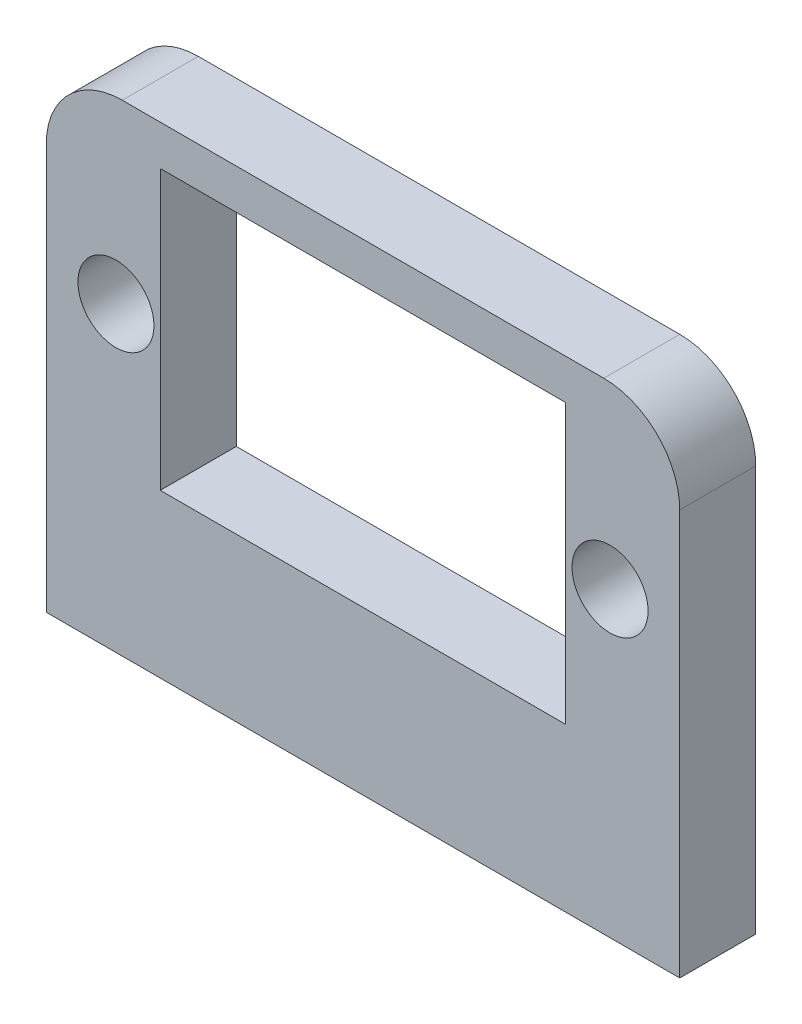
SolidWorks part; units mm, degrees
ref_plane "Front Plane" through (0, 0, 0) normal (0, 0, 1) x (1, 0, 0)
ref_plane "Top Plane" through (0, 0, 0) normal (0, 1, 0) x (1, 0, 0)
ref_plane "Right Plane" through (0, 0, 0) normal (1, 0, 0) x (0, 0, -1)
sketch "Sketch3" plane through (0, 0, 0) normal (0, 1, 0) x (1, 0, 0)
  line L0 (84.4541, 599.5572) -> (574.4541, 599.5572) construction
sketch "Sketch2" plane through (0, 0, 0) normal (0, 1, 0) x (1, 0, 0)
  line L0 (0, 0) -> (0, 57.603) construction
  line L1 (-18.1438, -7.9279) -> (18.1438, -7.9279) construction
  line L2 (-18.1438, -7.9279) -> (-18.1438, 7.9279) construction
  line L3 (-18.1438, 7.9279) -> (18.1438, 7.9279) construction
  line L4 (18.1438, -7.9279) -> (18.1438, 7.9279) construction
  line L5 (-18.1438, -7.9279) -> (18.1438, 7.9279) construction
  line L6 (-18.1438, 7.9279) -> (18.1438, -7.9279) construction
  line L7 (-21.8576, -11.143) -> (21.8576, -11.143) construction
  line L8 (-21.8576, -11.143) -> (-21.8576, 11.143) construction
  line L9 (-21.8576, 11.143) -> (21.8576, 11.143) construction
  line L10 (21.8576, -11.143) -> (21.8576, 11.143) construction
  line L11 (-21.8576, -11.143) -> (21.8576, 11.143) construction
  line L12 (-21.8576, 11.143) -> (21.8576, -11.143) construction
  line L13 (-8.5, 0) -> (8.5, 0) construction
  line L14 (0, 0) -> (0, -8.8619) construction
  line L15 (-20.6395, 7.1502) -> (-17.9674, 9.1598)
  line L16 (-4.1695, 10.4244) -> (4.1695, 10.4244)
  line L17 (-1.5343, -5.6375) -> (1.5343, -5.6375)
  line L18 (-10.0901, -10.3942) -> (-7.3916, -11.6987)
  line L19 (20.6395, 7.1502) -> (17.9674, 9.1598)
  line L20 (-2.2241, 10.4244) -> (-0.6961, 13.1148)
  line L21 (-0.6961, 13.1148) -> (0, 13.358)
  line L22 (2.2241, 10.4244) -> (0.6961, 13.1148)
  line L23 (0.6961, 13.1148) -> (0, 13.358)
  line L24 (-7.3916, -11.6987) -> (-0.7757, -11.143)
  line L25 (-0.7757, -11.143) -> (0, -10.9595)
  line L26 (0.7757, -11.143) -> (0, -10.9595)
  line L27 (7.3916, -11.6987) -> (0.7757, -11.143)
  line L28 (10.0901, -10.3942) -> (7.3916, -11.6987)
  line L29 (-16.4215, -5.191) -> (-11.7373, -9.2961)
  line L30 (16.4215, -5.191) -> (11.7373, -9.2961)
  line L31 (-7.3916, -11.6987) -> (7.3916, -11.6987)
  line L33 (-32.5, -20.0045) -> (32.5, -20.0045)
  line L34 (-32.5, -20.0045) -> (-32.5, 20.0045)
  line L35 (-32.5, 20.0045) -> (32.5, 20.0045)
  line L36 (32.5, -20.0045) -> (32.5, 20.0045)
  line L37 (-32.5, -20.0045) -> (32.5, 20.0045) construction
  line L38 (-32.5, 20.0045) -> (32.5, -20.0045) construction
  arc A0 (-4.1695, 10.4244) -> (-17.9674, 9.1598) centre (-11.9148, 19.0269) cw
  arc A1 (-20.6395, 7.1502) -> (-19.3461, 0.6629) centre (-23.2364, 3.2599) cw
  arc A2 (-19.3461, 0.6629) -> (-18.559, -3.0217) centre (-15.82, -0.5102) ccw
  arc A3 (-18.559, -3.0217) -> (-13.7831, -6.7121) centre (-9.4985, 3.7682) ccw
  arc A4 (-13.7831, -6.7121) -> (-6.6237, -7.9279) centre (-4.6259, 25.5245) ccw
  arc A5 (-1.5343, -5.6375) -> (-6.6237, -7.9279) centre (-1.5343, -12.4372) ccw
  arc A7 (13.7831, -6.7121) -> (6.6237, -7.9279) centre (4.6259, 25.5245) cw
  arc A8 (18.559, -3.0217) -> (13.7831, -6.7121) centre (9.4985, 3.7682) cw
  arc A9 (19.3461, 0.6629) -> (18.559, -3.0217) centre (15.82, -0.5102) cw
  arc A10 (20.6395, 7.1502) -> (19.3461, 0.6629) centre (23.2364, 3.2599) ccw
  arc A11 (4.1695, 10.4244) -> (17.9674, 9.1598) centre (11.9148, 19.0269) ccw
  arc A12 (1.5343, -5.6375) -> (6.6237, -7.9279) centre (1.5343, -12.4372) cw
  arc A14 (-12.2767, -7.1024) -> (-11.7373, -9.2961) centre (-8.8887, -7.4325) ccw
  arc A15 (-11.7373, -9.2961) -> (-10.0901, -10.3942) centre (-8.5052, -6.2323) ccw
  arc A16 (12.2767, -7.1024) -> (11.7373, -9.2961) centre (8.8887, -7.4325) cw
  arc A17 (11.7373, -9.2961) -> (10.0901, -10.3942) centre (8.5052, -6.2323) cw
  point P0 (0, 0)
  point P6 (0, 0)
  point P34 (0, 0)
  point P45 (0, 10.4244)
  point P54 (0, -5.6375)
  point P57 (-0.2087, -5.6375)
  point P72 (0, -11.6987)
  dimension "D2" = 65
  dimension "D1" = 17
extrude "Boss-Extrude1" add sketch "Sketch2" along normal blind 2
sketch "Sketch4" plane through (0, 0, 0) normal (0, 1, 0) x (1, 0, 0)
  line L0 (0, 0) -> (0, -15.9627) construction
  line L1 (0, 0) -> (0, 46.0631) construction
scale "Scale1" bodies to scale 101 scale about centroid uniform scaling yes scale factor 2
sketch "Sketch6" plane through (0, 3, 0) normal (0, 1, 0) x (1, 0, 0)
  line L0 (0, 0) -> (0, 27.4099) construction
  circle A0 centre (-5.8515, 16.2836) radius 1.5 construction
  circle A1 centre (-5.8515, 16.2836) radius 1.5
  circle A2 centre (4.1518, 16.2836) radius 1.5 construction
  circle A3 centre (4.1518, 16.2836) radius 1.5
extrude "Cut-Extrude2" cut sketch "Sketch6" against normal blind 3
sketch "Sketch7" plane through (0, 3, 0) normal (0, 1, 0) x (1, 0, 0)
  line L0 (0, 0) -> (0, 46.0631) construction
  line L1 (-12.5, 13.1109) -> (12.5, 13.1109)
  line L2 (-12.5, 13.1109) -> (-12.5, 10.1109)
  line L3 (-12.5, 10.1109) -> (12.5, 10.1109)
  line L4 (12.5, 13.1109) -> (12.5, 10.1109)
  line L5 (-12.5, 13.1109) -> (12.5, 10.1109) construction
  line L6 (-12.5, 10.1109) -> (12.5, 13.1109) construction
  point P0 (0, 11.6109)
  dimension "D1" = 3
  dimension "D2" = 25
extrude "Boss-Extrude2" add sketch "Sketch7" along normal blind 15
sketch "Sketch8" plane through (0, 0, -10.1109) normal (0, 0, 1) x (1, 0, 0)
  line L0 (0, 2.6097) -> (0, 7.1828) construction
  line L1 (-8, 16.4174) -> (8, 16.4174)
  line L2 (-8, 16.4174) -> (-8, 5.4174)
  line L3 (-8, 5.4174) -> (8, 5.4174)
  line L4 (8, 16.4174) -> (8, 5.4174)
  circle A0 centre (-9.75, 10.9174) radius 1.5
  circle A1 centre (9.75, 10.9174) radius 1.5
  point P4 (0, 5.4174)
  point P8 (-8, 10.9174)
  dimension "D3" = 3
  dimension "D4" = 1.75
  dimension "D1" = 16
  dimension "D2" = 11
extrude "Cut-Extrude3" cut sketch "Sketch8" against normal blind 18
fillet "Fillet3" radius 3 1 edges at (-12.5, 18, -11.6109)
fillet "Fillet4" radius 3 1 edges at (12.5, 18, -11.6109)
sketch "Sketch9" plane through (0, 3, 0) normal (0, 1, 0) x (1, 0, 0)
  line L21 (-7.6951, -21.8709) -> (-7.6951, -30.6829)
  line L22 (-7.6951, -30.6829) -> (5.9954, -30.6829)
  line L23 (5.9954, -30.6829) -> (5.9954, -21.8709)
  line L24 (5.9954, -21.8709) -> (8.9954, -21.8709)
  line L25 (8.9954, -21.8709) -> (8.9954, -30.0705)
  line L26 (8.9954, -30.0705) -> (18.6231, -24.4632)
  line L27 (18.6231, -24.4632) -> (23.9122, -21.0338)
  line L28 (25.28, -18.5167) -> (25.28, -3.348)
  line L29 (24.6327, -1.4865) -> (9.0527, 18.2043)
  line L30 (6.7, 19.3428) -> (3.3097, 19.3428)
  line L31 (3.3097, 19.3428) -> (0.5459, 24.5621)
  line L32 (0.5459, 24.5621) -> (-0.8499, 25.1844)
  line L33 (-0.8499, 25.1844) -> (-2.2456, 24.5621)
  line L34 (-2.2456, 24.5621) -> (-5.0094, 19.3428)
  line L35 (-5.0094, 19.3428) -> (-8.3997, 19.3428)
  line L36 (-10.7524, 18.2043) -> (-26.3324, -1.4865)
  line L37 (-26.9797, -3.348) -> (-26.9797, -18.5167)
  line L38 (-25.6119, -21.0338) -> (-20.3228, -24.4632)
  line L39 (-20.3228, -24.4632) -> (-10.6951, -30.0705)
  line L40 (-10.6951, -30.0705) -> (-10.6951, -21.8709)
  line L41 (-10.6951, -21.8709) -> (-7.6951, -21.8709)
  line L42 (-7.6951, -21.8709) -> (-7.6951, -30.6829)
  line L43 (-7.6951, -30.6829) -> (5.9954, -30.6829)
  line L44 (5.9954, -30.6829) -> (5.9954, -21.8709)
  line L45 (5.9954, -21.8709) -> (8.9954, -21.8709)
  line L46 (8.9954, -21.8709) -> (8.9954, -30.0705)
  line L47 (8.9954, -30.0705) -> (18.6231, -24.4632)
  line L48 (18.6231, -24.4632) -> (23.9122, -21.0338)
  line L49 (25.28, -18.5167) -> (25.28, -3.348)
  line L50 (24.6327, -1.4865) -> (9.0527, 18.2043)
  line L51 (6.7, 19.3428) -> (3.3097, 19.3428)
  line L52 (3.3097, 19.3428) -> (0.5459, 24.5621)
  line L53 (0.5459, 24.5621) -> (-0.8499, 25.1844)
  line L54 (-0.8499, 25.1844) -> (-2.2456, 24.5621)
  line L55 (-2.2456, 24.5621) -> (-5.0094, 19.3428)
  line L56 (-5.0094, 19.3428) -> (-8.3997, 19.3428)
  line L57 (-10.7524, 18.2043) -> (-26.3324, -1.4865)
  line L58 (-26.9797, -3.348) -> (-26.9797, -18.5167)
  line L59 (-25.6119, -21.0338) -> (-20.3228, -24.4632)
  line L60 (-20.3228, -24.4632) -> (-10.6951, -30.0705)
  line L61 (-10.6951, -30.0705) -> (-10.6951, -21.8709)
  line L62 (-10.6951, -21.8709) -> (-7.6951, -21.8709)
  arc A6 (23.9122, -21.0338) -> (25.28, -18.5167) centre (22.28, -18.5167) ccw
  arc A7 (25.28, -3.348) -> (24.6327, -1.4865) centre (22.28, -3.348) ccw
  arc A8 (9.0527, 18.2043) -> (6.7, 19.3428) centre (6.7, 16.3428) ccw
  arc A9 (-8.3997, 19.3428) -> (-10.7524, 18.2043) centre (-8.3997, 16.3428) ccw
  arc A10 (-26.3324, -1.4865) -> (-26.9797, -3.348) centre (-23.9797, -3.348) ccw
  arc A11 (-26.9797, -18.5167) -> (-25.6119, -21.0338) centre (-23.9797, -18.5167) ccw
  arc A12 (23.9122, -21.0338) -> (25.28, -18.5167) centre (22.28, -18.5167) ccw
  arc A13 (25.28, -3.348) -> (24.6327, -1.4865) centre (22.28, -3.348) ccw
  arc A14 (9.0527, 18.2043) -> (6.7, 19.3428) centre (6.7, 16.3428) ccw
  arc A15 (-8.3997, 19.3428) -> (-10.7524, 18.2043) centre (-8.3997, 16.3428) ccw
  arc A16 (-26.3324, -1.4865) -> (-26.9797, -3.348) centre (-23.9797, -3.348) ccw
  arc A17 (-26.9797, -18.5167) -> (-25.6119, -21.0338) centre (-23.9797, -18.5167) ccw
  dimension "D1" = 0
sketch "Sketch10" plane through (0, 3, 0) normal (0, 1, 0) x (1, 0, 0)
  circle A0 centre (-0.8499, -20.8953) radius 1.5 construction
  circle A1 centre (-0.8499, -20.8953) radius 1.5
extrude "Cut-Extrude4" cut sketch "Sketch10" against normal blind 10
sketch "Sketch11" plane through (0, 3, 0) normal (0, 1, 0) x (1, 0, 0)
  line L1 (-12.5, 13.1109) -> (12.5, 13.1109)
  line L2 (-12.5, 13.1109) -> (-12.5, 10.1109)
  line L3 (-12.5, 10.1109) -> (12.5, 10.1109)
  line L4 (12.5, 13.1109) -> (12.5, 10.1109)
  circle A0 centre (0, 0) radius 44.4401
extrude "Cut-Extrude5" cut sketch "Sketch11" against normal through all both
